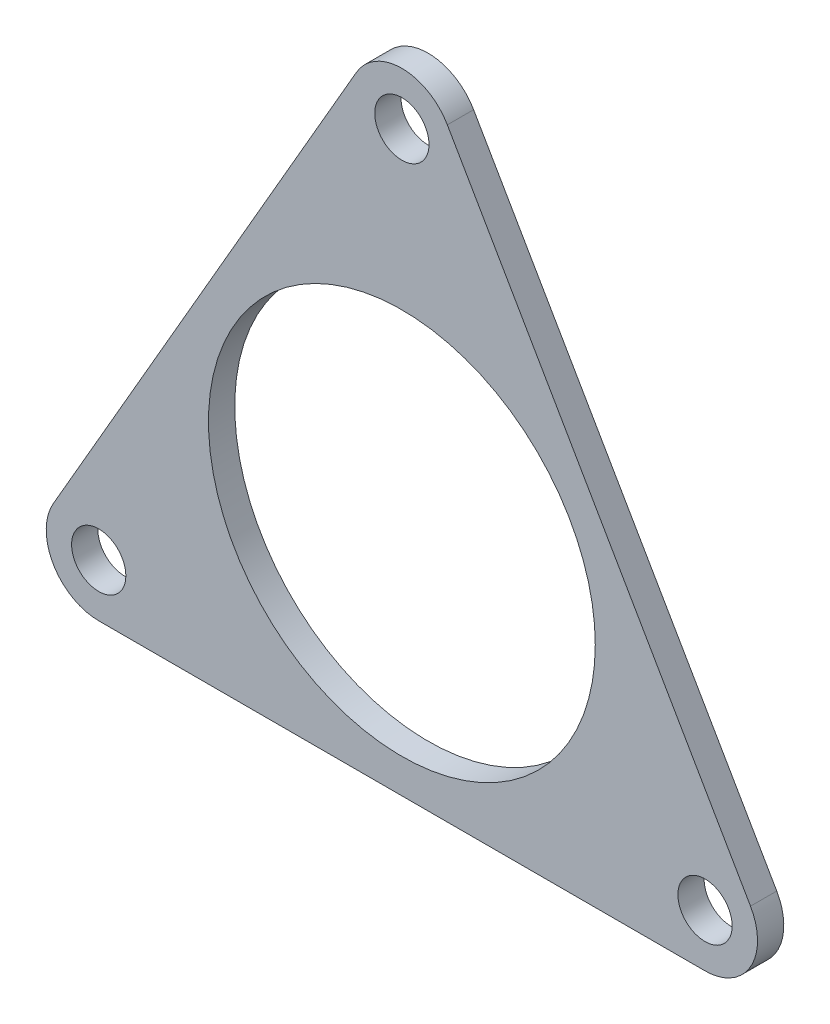
SolidWorks part; units mm, degrees
material "Thornel Mat VMA"
ref_plane "前视基准面" through (0, 0, 0) normal (0, 0, 1) x (1, 0, 0)
ref_plane "上视基准面" through (0, 0, 0) normal (0, 1, 0) x (1, 0, 0)
ref_plane "右视基准面" through (0, 0, 0) normal (1, 0, 0) x (0, 0, -1)
sketch "草图1" plane through (0, 0, 0) normal (0, 0, 1) x (1, 0, 0)
  line L0 (0, 20) -> (0, 0) construction
  line L1 (0, 0) -> (-17.3205, -10) construction
  line L2 (0, 0) -> (17.3205, -10) construction
  line L3 (-2.5981, 21.5) -> (-19.9186, -8.5)
  line L4 (2.5981, 21.5) -> (19.9186, -8.5)
  line L5 (-17.3205, -13) -> (17.3205, -13)
  circle A0 centre (0, 0) radius 20 construction
  circle A1 centre (0, 20) radius 1.55
  circle A2 centre (-17.3205, -10) radius 1.55
  circle A3 centre (17.3205, -10) radius 1.55
  arc A4 (2.5981, 21.5) -> (-2.5981, 21.5) centre (0, 20) ccw
  arc A5 (-19.9186, -8.5) -> (-17.3205, -13) centre (-17.3205, -10) ccw
  arc A6 (17.3205, -13) -> (19.9186, -8.5) centre (17.3205, -10) ccw
  dimension "D1" = 40
  dimension "D4" = 3.1
  dimension "D5" = 6
  dimension "D2" = 120
  dimension "D3" = 120
extrude "凸台-拉伸1" add sketch "草图1" along normal blind 1.5
sketch "草图2" plane through (0, 0, 1.5) normal (0, 0, 1) x (1, 0, 0)
  circle A0 centre (0, 0) radius 11.05
  dimension "D1" = 22.1
extrude "切除-拉伸1" cut sketch "草图2" against normal blind 1.5
